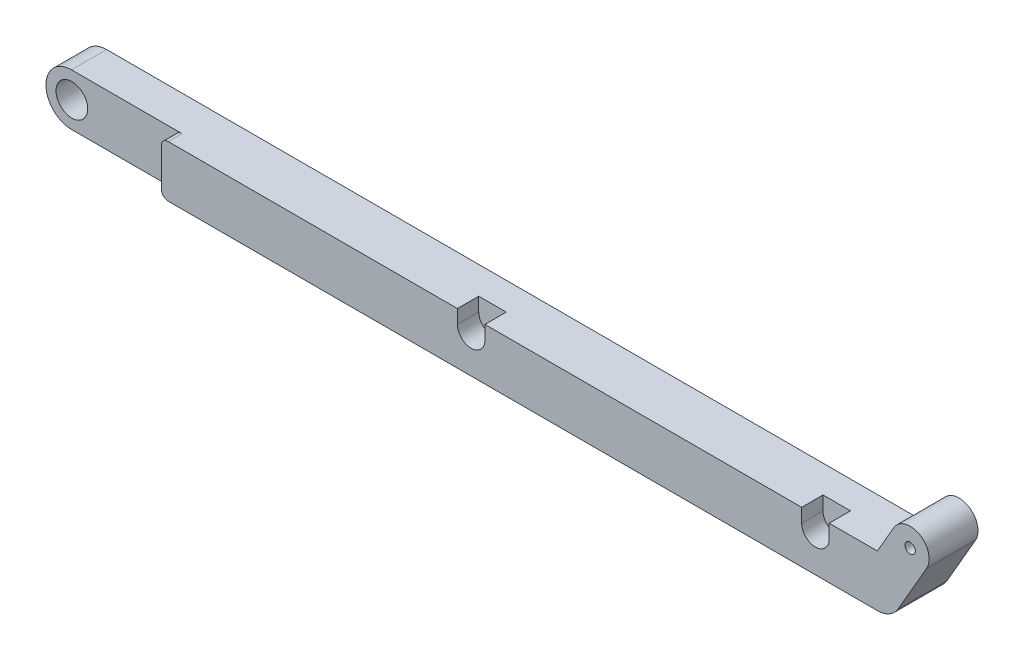
SolidWorks part; units mm, degrees
ref_plane "Front Plane" through (0, 0, 0) normal (0, 0, 1) x (1, 0, 0)
ref_plane "Top Plane" through (0, 0, 0) normal (0, 1, 0) x (1, 0, 0)
ref_plane "Right Plane" through (0, 0, 0) normal (1, 0, 0) x (0, 0, -1)
sketch "Sketch1" plane through (0, 0, 0) normal (0, 0, 1) x (1, 0, 0)
  line L0 (-126.25, 0) -> (-118.75, 0) construction
  line L1 (-118.85, 7.5) -> (-2.75, 7.5)
  line L2 (-126.25, 0.1) -> (-126.25, -0.1)
  line L3 (-118.85, -7.5) -> (119.25, -7.5)
  line L4 (126.25, 0.5) -> (126.25, -0.5) construction
  line L5 (-126.25, 7.5) -> (126.25, -7.5) construction
  line L6 (-126.25, -7.5) -> (126.25, 7.5) construction
  line L7 (-118.75, 0) -> (-118.75, 7.5) construction
  line L8 (-2.75, 3.5) -> (-2.75, 7.5)
  line L9 (5.25, 3.5) -> (5.25, 7.5)
  line L10 (5.25, 7.5) -> (97.25, 7.5)
  line L11 (97.25, 3.5) -> (97.25, 7.5)
  line L12 (105.25, 3.5) -> (105.25, 7.5)
  line L13 (105.25, 7.5) -> (119.25, 7.5)
  line L14 (119.25, 7.5) -> (124.0131, 15.75)
  line L15 (125.3122, -4) -> (133.5394, 10.25)
  line L19 (133.5394, 10.25) -> (124.0131, 15.75) construction
  circle A0 centre (-118.75, 0) radius 4.6
  arc A1 (97.25, 3.5) -> (105.25, 3.5) centre (101.25, 3.5) ccw
  arc A2 (-2.75, 3.5) -> (5.25, 3.5) centre (1.25, 3.5) ccw
  arc A3 (-126.25, -0.1) -> (-118.85, -7.5) centre (-118.85, -0.1) ccw
  arc A4 (-118.85, 7.5) -> (-126.25, 0.1) centre (-118.85, 0.1) ccw
  arc A5 (119.25, -7.5) -> (125.3122, -4) centre (119.25, -0.5) ccw
  arc A6 (119.25, 7.5) -> (126.25, 0.5) centre (119.25, 0.5) cw construction
  arc A7 (124.0131, 15.75) -> (133.5394, 10.25) centre (128.7763, 13) cw
  circle A8 centre (128.7763, 13) radius 1.5
  circle A10 centre (128.7763, 13) radius 5.5 construction
  point P0 (0, 0)
  point P47 (1.25, -0.5)
  dimension "D3" = 9.2
  dimension "D4" = 8
  dimension "D5" = 7.4
  dimension "D7" = 7
  dimension "D10" = 3
  dimension "D1" = 220
  dimension "D2" = 100
  dimension "D6" = 15
  dimension "D8" = 25
  dimension "D9" = 8
  dimension "D11" = 120
extrude "Boss-Extrude1" add sketch "Sketch1" along normal blind 10.2
sketch "Sketch2" plane through (0, 0, 0) normal (0, 0, -1) x (-1, 0, 0)
  line L0 (-105.25, 3.5) -> (-105.25, 7.5)
  line L1 (-105.25, 7.5) -> (-97.25, 7.5)
  line L2 (-97.25, 7.5) -> (-97.25, 3.5)
  line L3 (-5.25, 3.5) -> (-5.25, 7.5)
  line L4 (-5.25, 7.5) -> (2.75, 7.5)
  line L5 (2.75, 3.5) -> (2.75, 7.5) construction
  line L6 (2.75, 7.5) -> (2.75, 3.5)
  arc A0 (2.75, 3.5) -> (-5.25, 3.5) centre (-1.25, 3.5) cw
  arc A1 (-5.25, 3.5) -> (2.75, 3.5) centre (-1.25, 3.5) ccw construction
  arc A2 (-105.25, 3.5) -> (-97.25, 3.5) centre (-101.25, 3.5) ccw
extrude "Boss-Extrude2" add sketch "Sketch2" against normal blind 8
sketch "Sketch3" plane through (0, 0, 0) normal (0, 0, -1) x (-1, 0, 0)
  circle A0 centre (-128.7763, 13) radius 3.6
  dimension "D1" = 7.2
extrude "Cut-Extrude1" cut sketch "Sketch3" against normal blind 5
sketch "Sketch4" plane through (0, 0, 5) normal (0, 0, -1) x (-1, 0, 0)
  circle A0 centre (-128.7763, 13) radius 1.5 construction
  circle A1 centre (-128.7763, 13) radius 1.5
extrude "Boss-Extrude3" add sketch "Sketch4" against normal blind 0.6
sketch "Sketch5" plane through (0, 0, 10.2) normal (0, 0, 1) x (1, 0, 0)
  line L0 (-88.75, 7.5) -> (-88.75, -7.5)
  line L11 (97.25, 3.5) -> (97.25, 7.5)
  line L12 (97.25, 7.5) -> (5.25, 7.5)
  line L13 (5.25, 7.5) -> (5.25, 3.5)
  line L14 (-2.75, 3.5) -> (-2.75, 7.5)
  line L15 (-2.75, 7.5) -> (-118.85, 7.5)
  line L16 (-126.25, 0.1) -> (-126.25, -0.1)
  line L17 (-118.85, -7.5) -> (119.25, -7.5)
  line L18 (125.3122, -4) -> (133.5394, 10.25)
  line L19 (124.0131, 15.75) -> (119.25, 7.5)
  line L20 (119.25, 7.5) -> (105.25, 7.5)
  line L21 (105.25, 7.5) -> (105.25, 3.5)
  line L22 (97.25, 3.5) -> (97.25, 7.5)
  line L23 (97.25, 7.5) -> (5.25, 7.5)
  line L24 (5.25, 7.5) -> (5.25, 3.5)
  line L25 (-2.75, 3.5) -> (-2.75, 7.5)
  line L26 (-2.75, 7.5) -> (-88.75, 7.5)
  line L28 (-88.75, -7.5) -> (119.25, -7.5)
  line L29 (125.3122, -4) -> (133.5394, 10.25)
  line L30 (124.0131, 15.75) -> (119.25, 7.5)
  line L31 (119.25, 7.5) -> (105.25, 7.5)
  line L32 (105.25, 7.5) -> (105.25, 3.5)
  circle A0 centre (-118.75, 0) radius 4.6 construction
  circle A1 centre (128.7763, 13) radius 1.5 construction
  circle A2 centre (128.7763, 13) radius 1.5
  arc A6 (97.25, 3.5) -> (105.25, 3.5) centre (101.25, 3.5) ccw
  arc A7 (-2.75, 3.5) -> (5.25, 3.5) centre (1.25, 3.5) ccw
  arc A8 (-118.85, 7.5) -> (-126.25, 0.1) centre (-118.85, 0.1) ccw
  arc A9 (-126.25, -0.1) -> (-118.85, -7.5) centre (-118.85, -0.1) ccw
  arc A10 (119.25, -7.5) -> (125.3122, -4) centre (119.25, -0.5) ccw
  arc A11 (133.5394, 10.25) -> (124.0131, 15.75) centre (128.7763, 13) ccw
  arc A12 (97.25, 3.5) -> (105.25, 3.5) centre (101.25, 3.5) ccw
  arc A13 (-2.75, 3.5) -> (5.25, 3.5) centre (1.25, 3.5) ccw
  arc A16 (119.25, -7.5) -> (125.3122, -4) centre (119.25, -0.5) ccw
  arc A17 (133.5394, 10.25) -> (124.0131, 15.75) centre (128.7763, 13) ccw
  dimension "D2" = 30
  dimension "D1" = 0
extrude "Boss-Extrude4" add sketch "Sketch5" along normal blind 4
fillet "Fillet1" radius 2 2 edges at (-88.75, -7.5, 12.2) (-88.75, 7.5, 12.2)
